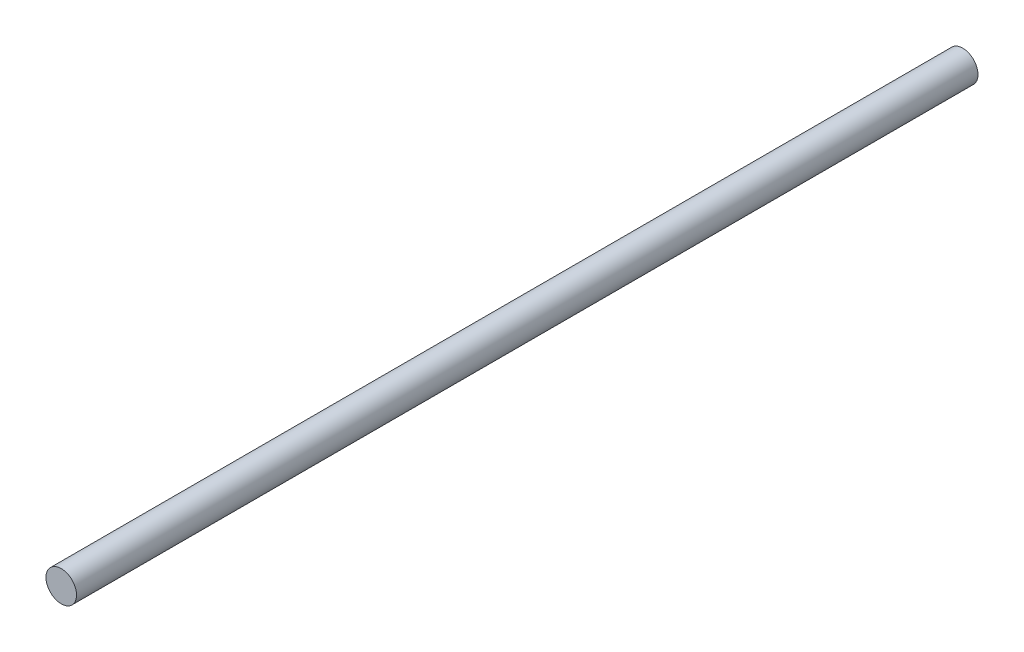
SolidWorks part; units mm, degrees
ref_plane "Alzado" through (0, 0, 0) normal (0, 0, 1) x (1, 0, 0)
ref_plane "Planta" through (0, 0, 0) normal (0, 1, 0) x (1, 0, 0)
ref_plane "Vista lateral" through (0, 0, 0) normal (1, 0, 0) x (0, 0, -1)
sketch "Croquis1" plane through (0, 0, 0) normal (0, 0, 1) x (1, 0, 0)
  circle A0 centre (0, 0) radius 6
extrude "Saliente-Extruir1" add sketch "Croquis1" along normal blind 354
